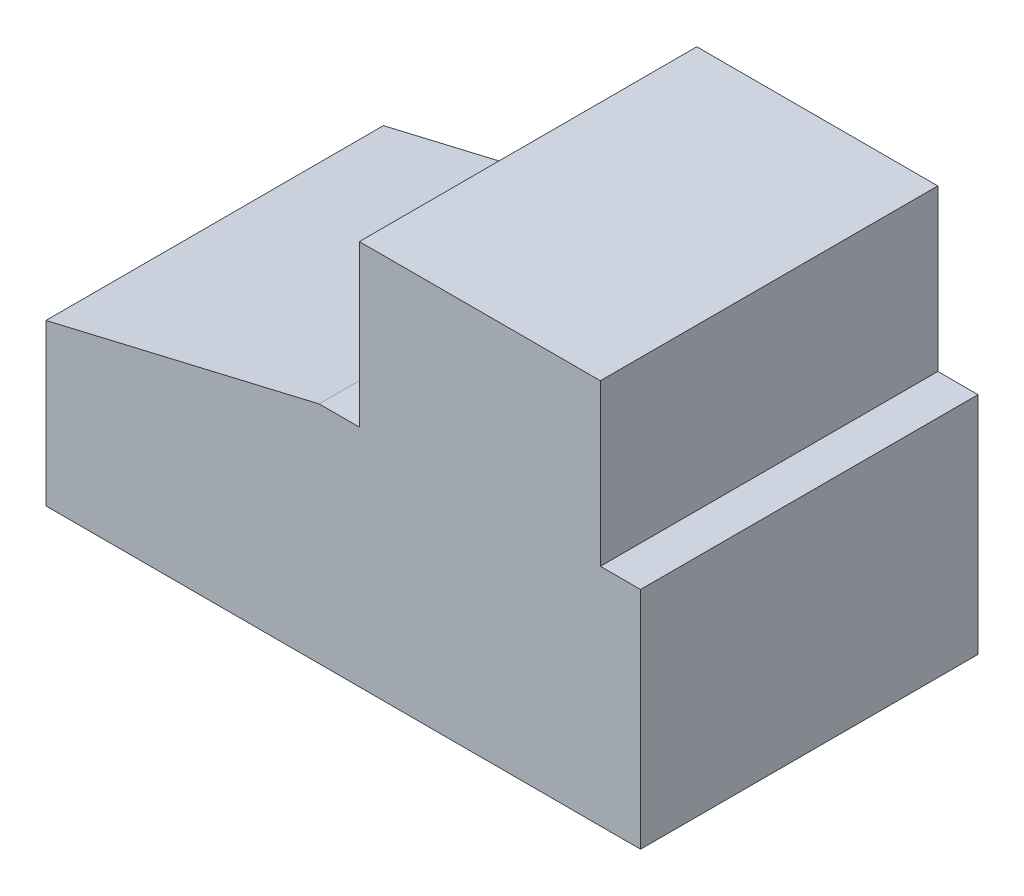
SolidWorks part; units mm, degrees
ref_plane "Front Plane" through (0, 0, 0) normal (0, 0, 1) x (1, 0, 0)
ref_plane "Top Plane" through (0, 0, 0) normal (0, 1, 0) x (1, 0, 0)
ref_plane "Right Plane" through (0, 0, 0) normal (1, 0, 0) x (0, 0, -1)
sketch "Sketch1" plane through (0, 0, 0) normal (0, 0, 1) x (1, 0, 0)
  line L0 (0, 20) -> (34, 28)
  line L1 (0, 0) -> (74, 0)
  line L2 (0, 0) -> (0, 20)
  line L3 (39, 48) -> (69, 48)
  line L4 (74, 0) -> (74, 28)
  line L5 (34, 28) -> (39, 28)
  line L6 (39, 48) -> (39, 28)
  line L7 (69, 48) -> (69, 28)
  line L8 (69, 28) -> (74, 28)
  dimension "D1" = 74
  dimension "D2" = 20
  dimension "D3" = 28
  dimension "D4" = 20
  dimension "D5" = 40
  dimension "D6" = 5
  dimension "D7" = 30
extrude "Boss-Extrude1" add sketch "Sketch1" along normal blind 42
sketch "Sketch2" plane through (0, 0, 0) normal (-1, 0, 0) x (0, 0, 1)
  line L4 (0, 20) -> (0, 0)
  line L5 (0, 0) -> (42, 0)
  line L6 (42, 0) -> (42, 20)
  line L7 (42, 20) -> (0, 20)
  line L8 (0, 20) -> (0, 0)
  line L9 (0, 0) -> (42, 0)
  line L10 (42, 0) -> (42, 20)
  line L11 (42, 20) -> (0, 20)
  circle A0 centre (21, 0) radius 7.0753
  dimension "D2" = 14.1507
  dimension "D1" = 0
